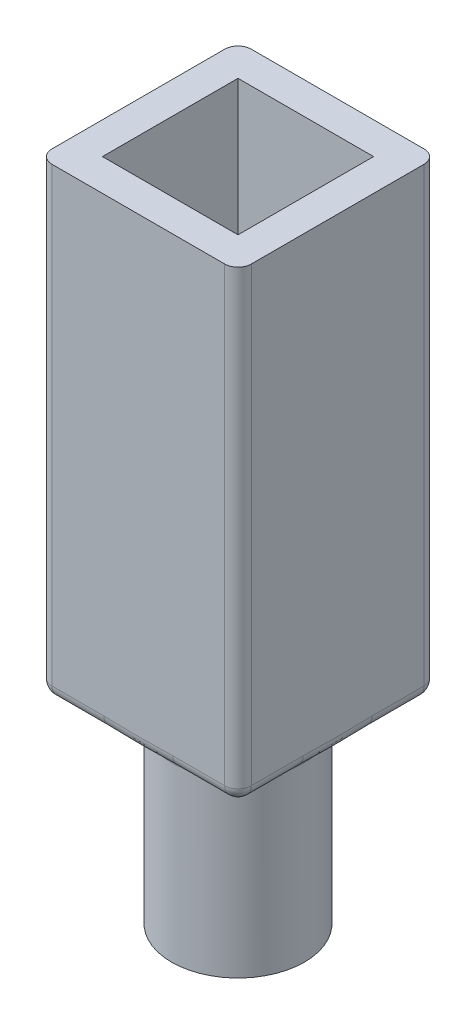
SolidWorks part; units mm, degrees
ref_plane "前视基准面" through (0, 0, 0) normal (0, 0, 1) x (1, 0, 0)
ref_plane "上视基准面" through (0, 0, 0) normal (0, 1, 0) x (1, 0, 0)
ref_plane "右视基准面" through (0, 0, 0) normal (1, 0, 0) x (0, 0, -1)
sketch "草图1" plane through (0, 0, 0) normal (0, 1, 0) x (1, 0, 0)
  circle A0 centre (0, 0) radius 5
  dimension "D1" = 10
extrude "凸台-拉伸1" add sketch "草图1" along normal blind 15 contours A0
sketch "草图2" plane through (0, 15, 0) normal (0, 1, 0) x (1, 0, 0)
  line L1 (7.5, 7.5) -> (-7.5, 7.5)
  line L2 (7.5, 7.5) -> (7.5, -7.5)
  line L3 (7.5, -7.5) -> (-7.5, -7.5)
  line L4 (-7.5, 7.5) -> (-7.5, -7.5)
  line L5 (7.5, 7.5) -> (-7.5, -7.5) construction
  line L6 (7.5, -7.5) -> (-7.5, 7.5) construction
  point P0 (0, 0)
  dimension "D1" = 15
  dimension "D2" = 15
extrude "凸台-拉伸2" add sketch "草图2" along normal blind 3
fillet "圆角1" radius 2 1 edges at (0, 15, 5)
sketch "草图3" plane through (0, 18, 0) normal (0, 1, 0) x (1, 0, 0)
  line L0 (7.5, 7.5) -> (-7.5, 7.5) construction
  line L1 (-7.5, 7.5) -> (-7.5, -7.5) construction
  line L2 (-7.5, -7.5) -> (7.5, -7.5) construction
  line L3 (7.5, -7.5) -> (7.5, 7.5) construction
  line L4 (7.5, 7.5) -> (-7.5, 7.5)
  line L5 (-7.5, 7.5) -> (-7.5, -7.5)
  line L6 (-7.5, -7.5) -> (7.5, -7.5)
  line L7 (7.5, -7.5) -> (7.5, 7.5)
  line L9 (5.1, -5.1) -> (-5.1, -5.1)
  line L10 (5.1, -5.1) -> (5.1, 5.1)
  line L11 (5.1, 5.1) -> (-5.1, 5.1)
  line L12 (-5.1, -5.1) -> (-5.1, 5.1)
  line L13 (5.1, -5.1) -> (-5.1, 5.1) construction
  line L14 (5.1, 5.1) -> (-5.1, -5.1) construction
  point P2 (0, 0)
  dimension "D1" = 2.4
  dimension "D2" = 2.4
extrude "凸台-拉伸3" add sketch "草图3" along normal blind 32
sketch "草图4" plane through (0, 0, 0) normal (0, -1, 0) x (1, 0, 0)
  line L0 (-1.85, -3.815) -> (-1.85, 3.3728)
  circle A0 centre (0, 0) radius 2.75
  dimension "D1" = 5.5
  dimension "D2" = 1.85
extrude "切除-拉伸1" cut sketch "草图4" against normal blind 10 contours L0 A0
fillet "圆角2" radius 1 8 edges at (0, 15, -7.5) (7.5, 15, 0) (-7.5, 15, 0) (0, 15, 7.5) (-7.5, 32.5, -7.5) (-7.5, 32.5, 7.5) (7.5, 32.5, -7.5) (7.5, 32.5, 7.5)
